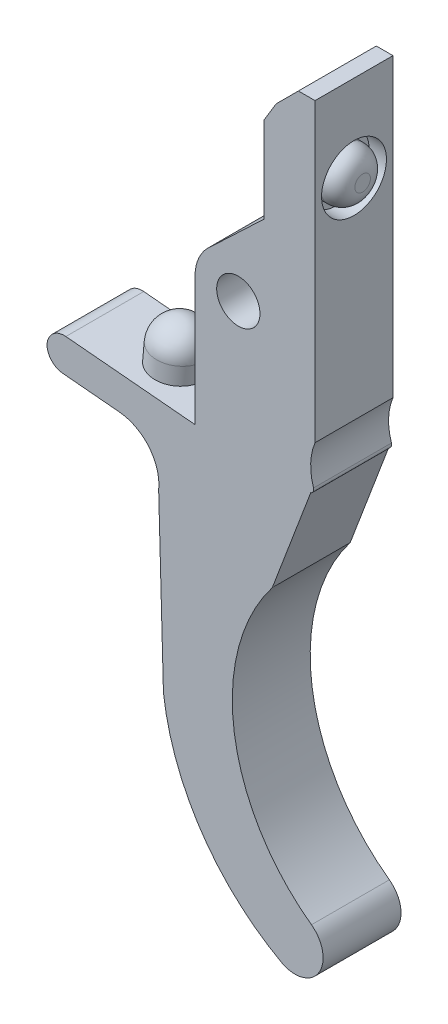
SolidWorks part; units mm, degrees
ref_plane "정면" through (0, 0, 0) normal (0, 0, 1) x (1, 0, 0)
ref_plane "윗면" through (0, 0, 0) normal (0, 1, 0) x (1, 0, 0)
ref_plane "우측면" through (0, 0, 0) normal (1, 0, 0) x (0, 0, -1)
sketch "스케치1" plane through (0, 0, 0) normal (0, 0, 1) x (1, 0, 0)
  line L0 (6.9421, 24.5013) -> (8.8664, 24.5013)
  line L1 (6.9421, 24.5013) -> (4.3842, 21.9434)
  line L2 (8.8664, 24.5013) -> (8.8664, -9.7282)
  line L3 (-5, 0) -> (-5, -14.8544)
  line L4 (-5, -14.8544) -> (-19.9215, -13.497)
  line L5 (2.9878, 19.65) -> (2.9878, 17.6612)
  line L6 (-20.2877, -17.3633) -> (-13.717, -17.9611)
  line L7 (2.9878, 17.6612) -> (2.9878, 9.7088)
  line L8 (2.9878, 9.7088) -> (-3.1847, 3.8546)
  line L9 (8.3701, -14.9782) -> (3.9243, -26.7023)
  line L10 (2.2148, 21.9434) -> (17.8049, 21.9434) construction
  line L11 (4.3842, 21.9434) -> (2.9878, 19.65)
  line L12 (-9.201, -23.497) -> (-8.6487, -43.505)
  circle A0 centre (0, 0) radius 2.5
  circle A1 centre (0, 0) radius 5
  arc A2 (-8.6487, -43.505) -> (5.1786, -63.7713) centre (17.9124, -40.233) ccw
  arc A5 (-22.1027, -15.4958) -> (-20.2877, -17.3633) centre (-20.1065, -15.3716) ccw
  arc A6 (-19.9215, -13.497) -> (-22.1027, -15.4958) centre (-20.1027, -15.4887) ccw
  arc A7 (8.8664, -9.7282) -> (8.6919, -14.3466) centre (15.0215, -12.2733) ccw
  arc A8 (8.6919, -14.3466) -> (8.3701, -14.9782) centre (8.2168, -14.5023) cw
  arc A9 (-13.717, -17.9611) -> (-9.201, -23.497) centre (-14.17, -22.9405) cw
  arc A10 (3.9243, -26.7023) -> (8.453, -58.1684) centre (21.4542, -40.2383) ccw
  arc A11 (5.1786, -63.7713) -> (8.453, -58.1684) centre (6.539, -60.8081) ccw
  dimension "D1" = 5
  dimension "D2" = 10
  dimension "D4" = 2
  dimension "D5" = 0.5
  dimension "D6" = 5
  dimension "D3" = 45
extrude "보스-돌출1" add sketch "스케치1" along normal blind 9
sketch "스케치2" plane through (8.8664, 0, 0) normal (1, 0, 0) x (0, 0, -1)
  line L0 (-9, 24.5013) -> (0, 24.5013) construction
  circle A0 centre (-4.5, 14.5013) radius 3.75
  dimension "D1" = 7.5
  dimension "D2" = 10
extrude "컷-돌출1" cut sketch "스케치2" against normal blind 2
sketch "스케치3" plane through (6.8664, 0, 0) normal (1, 0, 0) x (0, 0, -1)
  circle A0 centre (-4.5, 14.5013) radius 2.9
  dimension "D1" = 5.8
extrude "보스-돌출2" add sketch "스케치3" along normal blind 3
fillet "필렛1" radius 2 1 edges at (9.8664, 17.4013, 4.5)
sketch "스케치4" plane through (-1.3813, -15.1836, 0) normal (0.0906, 0.9959, 0) x (0.9959, -0.0906, 0)
  line L0 (-3.6336, -9) -> (-3.6336, 0) construction
  circle A0 centre (-10.1336, -4.5) radius 2.9
  point P2 (-3.6336, -4.5)
  dimension "D1" = 5.8
  dimension "D2" = 6.5
extrude "보스-돌출3" add sketch "스케치4" along normal blind 5
fillet "필렛2" radius 2.9 1 edges at (-13.9083, -9.0234, 4.5)
